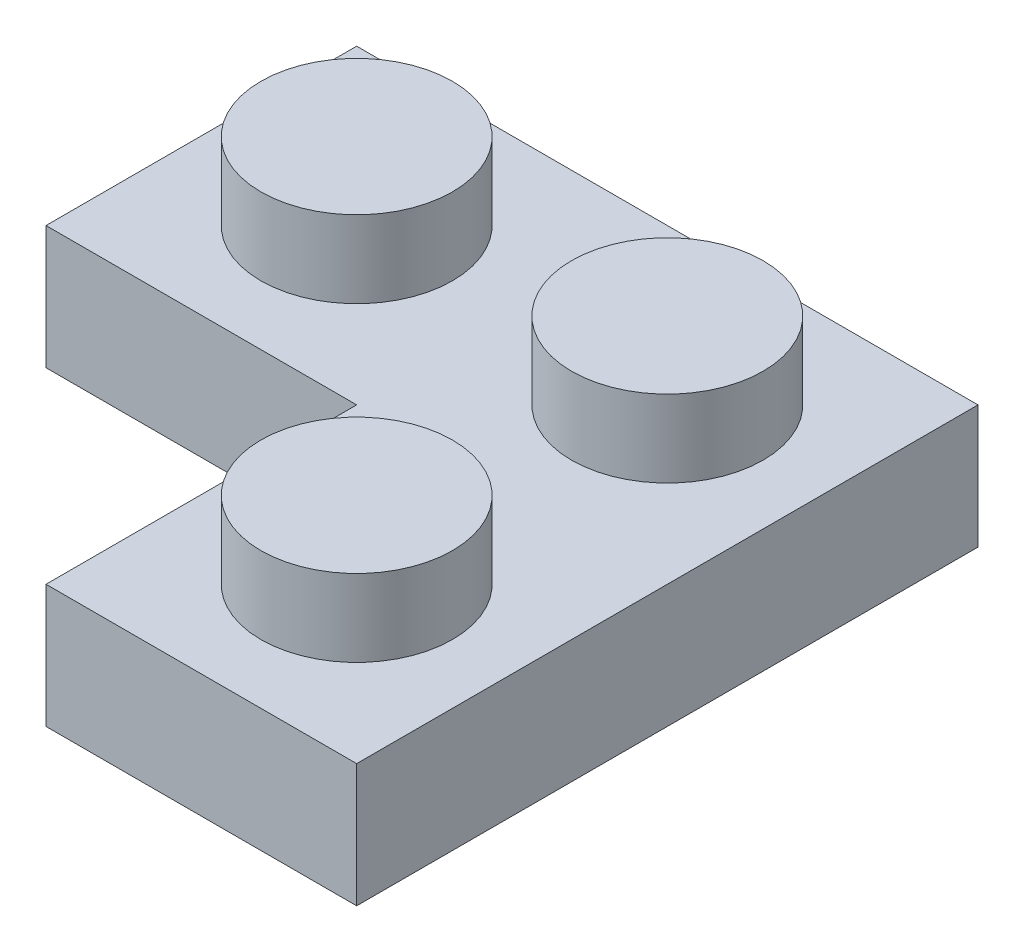
SolidWorks part; units mm, degrees
ref_plane "Front Plane" through (0, 0, 0) normal (0, 0, 1) x (1, 0, 0)
ref_plane "Top Plane" through (0, 0, 0) normal (0, 1, 0) x (1, 0, 0)
ref_plane "Right Plane" through (0, 0, 0) normal (1, 0, 0) x (0, 0, -1)
sketch "Sketch1" plane through (0, 0, 0) normal (0, 1, 0) x (1, 0, 0)
  line L0 (0, 0) -> (0, -7.945)
  line L1 (0, -7.945) -> (7.945, -7.945)
  line L2 (7.945, -7.945) -> (7.945, 7.945)
  line L3 (7.945, 7.945) -> (-7.945, 7.945)
  line L4 (-7.945, 7.945) -> (-7.945, 0)
  line L5 (-7.945, 0) -> (0, 0)
  point P7 (0, 0)
  point P8 (7.945, 0)
  point P9 (0, 0)
  point P10 (0, 7.945)
  dimension "D1" = 15.89
  dimension "D2" = 15.89
extrude "Boss-Extrude1" add sketch "Sketch1" against normal blind 3.15
sketch "Sketch2" plane through (0, 0, 0) normal (0, 1, 0) x (1, 0, 0)
  line L1 (7.945, -7.945) -> (7.945, 7.945) construction
  line L2 (7.945, 7.945) -> (-7.945, 7.945) construction
  line L3 (0, -7.945) -> (7.945, -7.945) construction
  line L4 (-7.945, 7.945) -> (-7.945, 0) construction
  circle A0 centre (3.9725, 3.9725) radius 2.45
  circle A1 centre (3.9725, -3.9725) radius 2.45
  circle A2 centre (-3.9725, 3.9725) radius 2.45
  dimension "D1" = 3.9725
  dimension "D3" = 4.9
  dimension "D4" = 3.9725
  dimension "D6" = 4.9
  dimension "D9" = 4.9
  dimension "D2" = 3.9725
  dimension "D5" = 3.9725
  dimension "D7" = 3.9725
  dimension "D8" = 3.9725
extrude "Boss-Extrude2" add sketch "Sketch2" along normal blind 1.97
shell "Shell1" thickness 1.55
sketch "Sketch3" plane through (0, -1.55, 0) normal (0, -1, 0) x (1, 0, 0)
  line L1 (-7.945, 0) -> (0, 0) construction
  line L2 (7.945, 7.945) -> (7.945, -7.945) construction
  circle A0 centre (0, -3.975) radius 1.48
  circle A1 centre (0, -3.975) radius 0.54
  circle A2 centre (3.97, 0) radius 1.48
  circle A3 centre (3.97, 0) radius 0.54
  dimension "D2" = 3.975
  dimension "D3" = 2.96
  dimension "D4" = 2.96
  dimension "D5" = 1.08
  dimension "D6" = 1.08
  dimension "D1" = 3.975
extrude "Boss-Extrude3" add sketch "Sketch3" along normal offset from surface (1.4 mm away) 0.2 up to face at (0, -3.15, 0)
